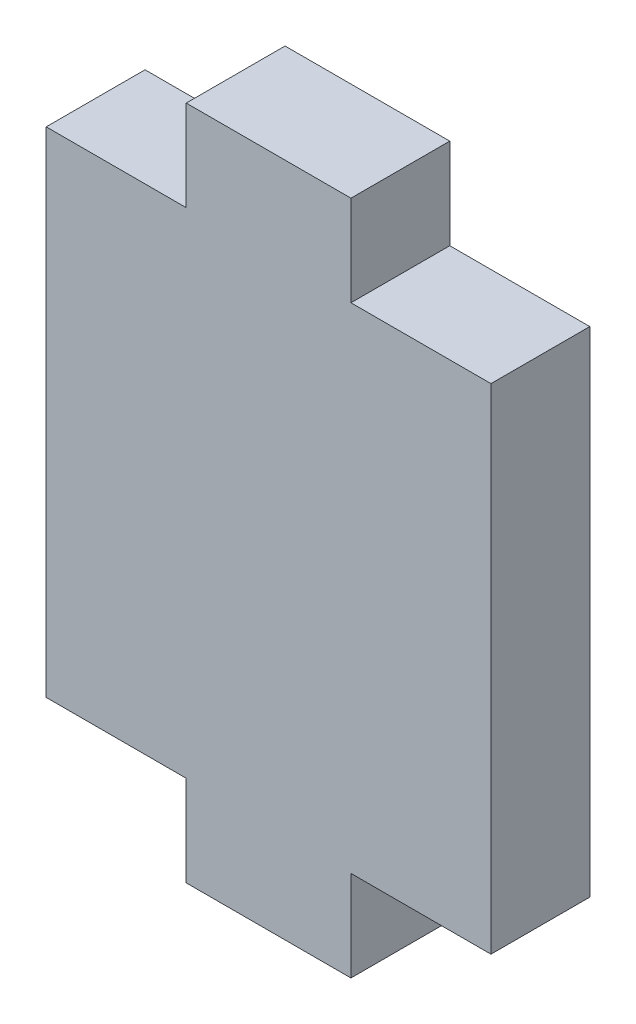
SolidWorks part; units mm, degrees
ref_plane "Front Plane" through (0, 0, 0) normal (0, 0, 1) x (1, 0, 0)
ref_plane "Top Plane" through (0, 0, 0) normal (0, 1, 0) x (1, 0, 0)
ref_plane "Right Plane" through (0, 0, 0) normal (1, 0, 0) x (0, 0, -1)
sketch "Sketch1" plane through (0, 0, 0) normal (0, 0, 1) x (1, 0, 0)
  line L0 (5, -15) -> (13.5, -15)
  line L1 (-13.5, -15) -> (-5, -15)
  line L2 (-13.5, -15) -> (-13.5, 15)
  line L3 (-13.5, 15) -> (-5, 15)
  line L4 (13.5, -15) -> (13.5, 15)
  line L5 (-13.5, -15) -> (13.5, 15) construction
  line L6 (-13.5, 15) -> (13.5, -15) construction
  line L8 (5, 15) -> (5, 20.5)
  line L9 (5, 20.5) -> (-5, 20.5)
  line L10 (-5, 15) -> (-5, 20.5)
  line L12 (5, -15) -> (5, -20.5)
  line L13 (5, -20.5) -> (-5, -20.5)
  line L14 (-5, -15) -> (-5, -20.5)
  line L15 (5, 15) -> (13.5, 15)
  line L16 (0, -25.7964) -> (0, 25.7271) construction
  line L17 (-35.3878, 0) -> (40.7202, 0) construction
  point P0 (0, 0)
  point P16 (0, 20.5)
  point P17 (0, -20.5)
  point P20 (13.5, 0)
  point P21 (-13.5, 0)
  dimension "D1" = 30
  dimension "D2" = 10
  dimension "D3" = 8.5
  dimension "D4" = 5.5
extrude "Boss-Extrude1" add sketch "Sketch1" along normal blind 6
